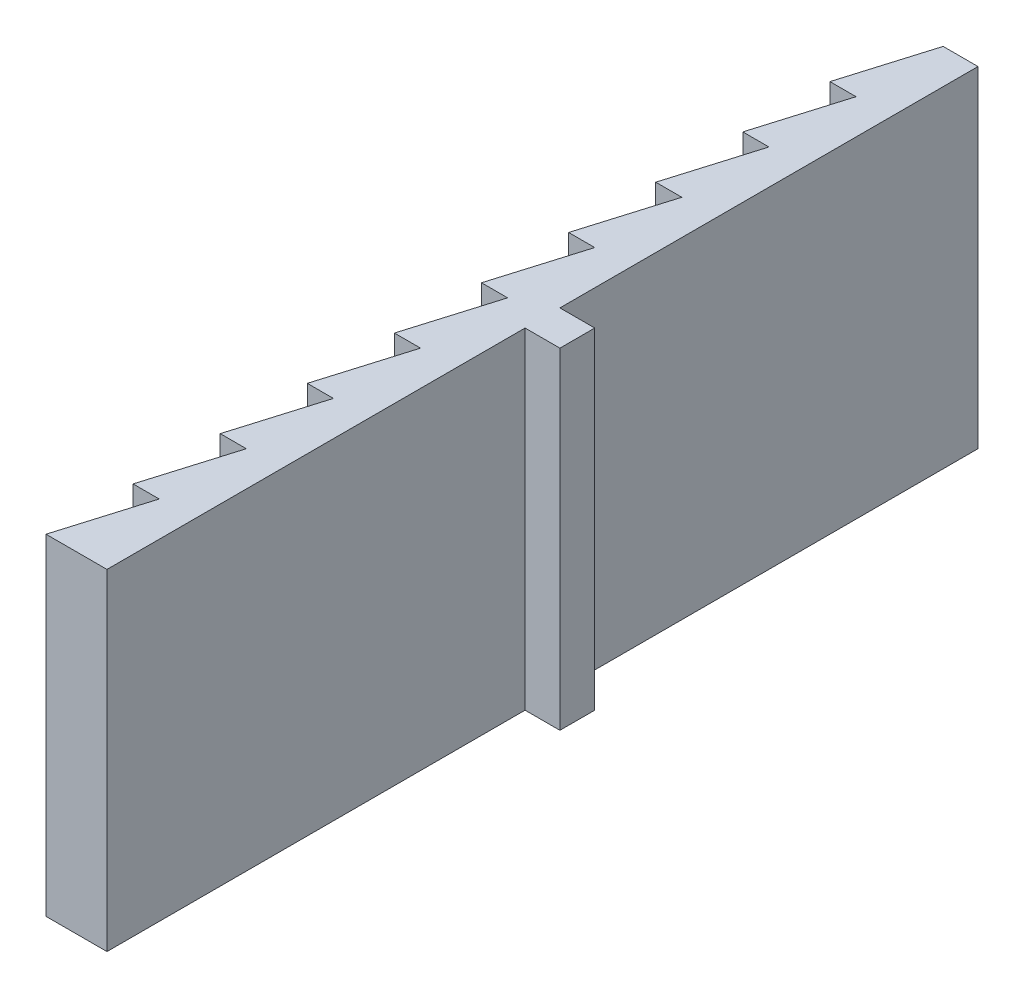
SolidWorks part; units mm, degrees
ref_plane "Front Plane" through (0, 0, 0) normal (0, 0, 1) x (1, 0, 0)
ref_plane "Top Plane" through (0, 0, 0) normal (0, 1, 0) x (1, 0, 0)
ref_plane "Right Plane" through (0, 0, 0) normal (1, 0, 0) x (0, 0, -1)
sketch "Sketch1" plane through (0, 0, 0) normal (0, 1, 0) x (1, 0, 0)
  line L0 (0, 0) -> (0, 25)
  line L1 (0, 25) -> (-1, 25)
  line L2 (-1, 25) -> (-1, 0)
  line L3 (-1, 0) -> (0, 0)
  line L4 (-1, 25) -> (-1.75, 22.5)
  line L5 (-1.75, 22.5) -> (-1, 22.5)
  line L6 (-1, 22.5) -> (-1, 25)
  line L7 (-1, 22.5) -> (-1.75, 20)
  line L8 (-1.75, 20) -> (-1, 20)
  line L9 (-1, 20) -> (-1, 22.5)
  line L10 (-1, 20) -> (-1.75, 17.5)
  line L11 (-1.75, 17.5) -> (-1, 17.5)
  line L12 (-1, 17.5) -> (-1, 20)
  line L13 (-1, 17.5) -> (-1.75, 15)
  line L14 (-1.75, 15) -> (-1, 15)
  line L15 (-1, 15) -> (-1, 17.5)
  line L16 (-1, 15) -> (-1.75, 12.5)
  line L17 (-1.75, 12.5) -> (-1, 12.5)
  line L18 (-1, 12.5) -> (-1, 15)
  line L19 (-1, 12.5) -> (-1.75, 10)
  line L20 (-1.75, 10) -> (-1, 10)
  line L21 (-1, 10) -> (-1, 12.5)
  line L22 (-1, 10) -> (-1.75, 7.5)
  line L23 (-1.75, 7.5) -> (-1, 7.5)
  line L24 (-1, 7.5) -> (-1, 10)
  line L25 (-1, 7.5) -> (-1.75, 5)
  line L26 (-1.75, 5) -> (-1, 5)
  line L27 (-1, 5) -> (-1, 7.5)
  line L28 (-1, 5) -> (-1.75, 2.5)
  line L29 (-1.75, 2.5) -> (-1, 2.5)
  line L30 (-1, 2.5) -> (-1, 5)
  line L31 (-1, 2.5) -> (-1.75, 0)
  line L32 (-1.75, 0) -> (-1, 0)
  line L33 (-1, 0) -> (-1, 2.5)
  dimension "D1" = 1
  dimension "D2" = 25
  dimension "D3" = 0.75
  dimension "D4" = 2.5
  dimension "D5" = 10
extrude "Boss-Extrude1" add sketch "Sketch1" along normal blind 9.5 contours L2 L3 L0 L1 | L4 L5 L2 | L7 L8 L2 | L10 L11 L2 | L13 L14 L2 | L16 L17 L2 | L19 L20 L2 | L22 L23 L2 | L25 L26 L2 | L31 L32 L2 | L29 L30 L28
sketch "Sketch2" plane through (0, 9.5, 0) normal (0, 1, 0) x (1, 0, 0)
  line L0 (0, 0) -> (0, 25) construction
  line L1 (0, 13) -> (1, 13)
  line L2 (0, 13) -> (0, 12)
  line L3 (0, 12) -> (1, 12)
  line L4 (1, 13) -> (1, 12)
  point P6 (0, 12.5)
  point P7 (1, 12.5)
  dimension "D1" = 1
  dimension "D2" = 1
extrude "Boss-Extrude2" add sketch "Sketch2" against normal blind 9.5
